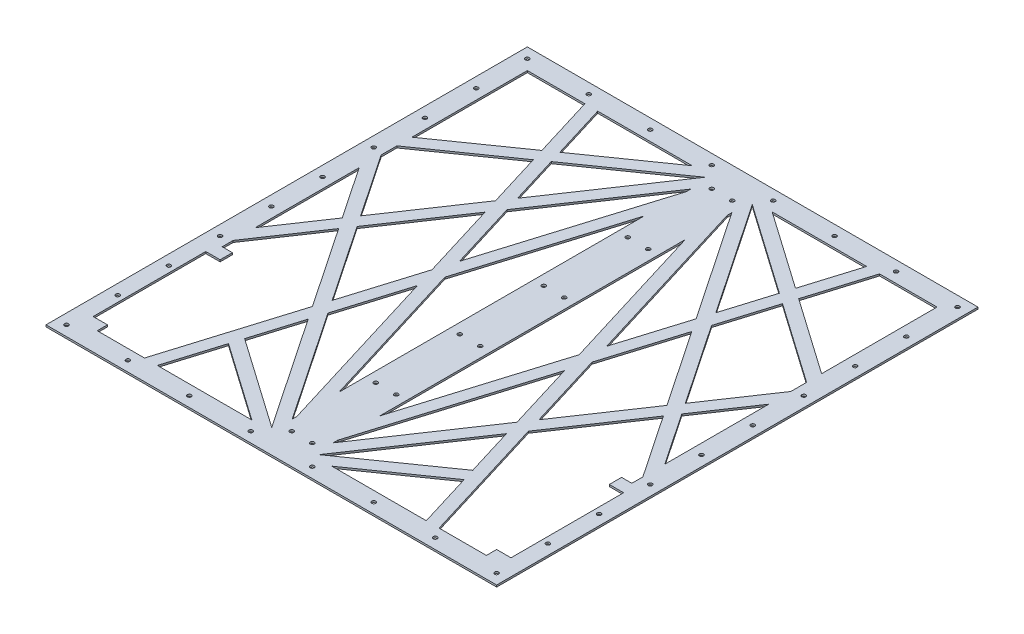
SolidWorks part; units mm, degrees
material "1060 Alloy"
ref_plane "Front Plane" through (0, 0, 0) normal (0, 0, 1) x (1, 0, 0)
ref_plane "Top Plane" through (0, 0, 0) normal (0, 1, 0) x (1, 0, 0)
ref_plane "Right Plane" through (0, 0, 0) normal (1, 0, 0) x (0, 0, -1)
sketch "Sketch1" plane through (0, 0, 0) normal (0, 1, 0) x (1, 0, 0)
  line L1 (0, 0) -> (558.8, 0)
  line L2 (0, 0) -> (0, 596.9)
  line L3 (0, 596.9) -> (558.8, 596.9)
  line L4 (558.8, 0) -> (558.8, 596.9)
  dimension "D1" = 596.9
  dimension "D2" = 558.8
extrude "Boss-Extrude1" add sketch "Sketch1" along normal blind 2.286 contours L2 L3 L4 L1
sketch "Sketch2" plane through (0, 2.286, 0) normal (0, 1, 0) x (1, 0, 0)
  line L0 (0, 0) -> (558.8, 0) construction
  line L1 (538.48, 38.1) -> (520.7, 38.1)
  line L2 (538.48, 38.1) -> (538.48, 177.8)
  line L3 (538.48, 177.8) -> (520.7, 177.8)
  line L4 (495.3, 76.2) -> (495.3, 139.7)
  line L5 (558.8, 0) -> (558.8, 596.9) construction
  line L6 (520.7, 177.8) -> (495.3, 139.7)
  line L7 (520.7, 38.1) -> (495.3, 76.2)
  dimension "D1" = 38.1
  dimension "D2" = 20.32
  dimension "D3" = 43.18
  dimension "D4" = 139.7
  dimension "D5" = 25.4
  dimension "D6" = 38.1
  dimension "D7" = 38.1
extrude "Cut-Extrude1" cut sketch "Sketch2" against normal through all
sketch "Sketch3" plane through (0, 2.286, 0) normal (0, 1, 0) x (1, 0, 0)
  line L0 (279.4, 596.9) -> (279.4, 0) construction
  line L1 (0, 596.9) -> (558.8, 596.9) construction
  line L2 (0, 0) -> (558.8, 0) construction
  line L3 (533.4, 571.5) -> (304.8, 571.5)
  line L4 (304.8, 571.5) -> (304.8, 25.4)
  line L5 (304.8, 25.4) -> (510.8505, 25.4)
  line L6 (510.8505, 25.4) -> (480.06, 71.5857)
  line L7 (480.06, 71.5857) -> (480.06, 144.3143)
  line L8 (480.06, 144.3143) -> (512.5438, 193.04)
  line L9 (512.5438, 193.04) -> (533.4, 193.04)
  line L10 (533.4, 193.04) -> (533.4, 571.5)
  line L11 (558.8, 0) -> (558.8, 596.9) construction
  line L12 (538.48, 177.8) -> (520.7, 177.8) construction
  line L14 (495.3, 139.7) -> (495.3, 76.2) construction
  line L15 (495.3, 76.2) -> (520.7, 38.1) construction
  line L16 (520.7, 177.8) -> (495.3, 139.7) construction
  dimension "D1" = 25.4
  dimension "D2" = 25.4
  dimension "D3" = 25.4
  dimension "D4" = 25.4
  dimension "D5" = 15.24
  dimension "D6" = 15.24
  dimension "D7" = 15.24
  dimension "D8" = 15.24
sketch "Sketch4" plane through (0, 2.286, 0) normal (0, 1, 0) x (1, 0, 0)
  line L0 (279.4, 0) -> (739.5052, 322.1692) construction
  line L1 (0, 0) -> (558.8, 0) construction
  line L3 (279.4, 0) -> (752.0221, 700.6911) construction
  line L5 (279.4, 0) -> (585.8425, 1002.3282) construction
  line L7 (279.4, 596.9) -> (1502.9036, -259.8065) construction
  line L8 (0, 596.9) -> (558.8, 596.9) construction
  line L9 (279.4, 596.9) -> (1021.4817, -503.2813) construction
  line L11 (279.4, 596.9) -> (643.6376, -594.4676) construction
  line L13 (286.687, -2.2279) -> (593.1295, 1000.1003)
  line L14 (285.7173, -4.261) -> (758.3394, 696.43)
  line L15 (283.7707, -6.2419) -> (738.0104, 311.8202)
  line L16 (272.113, 594.6721) -> (636.3506, -596.6955)
  line L17 (273.0827, 592.639) -> (1015.1644, -507.5424)
  line L18 (275.0293, 590.6581) -> (1498.533, -266.0484)
  line L19 (272.113, 2.2279) -> (578.5554, 1004.556)
  line L20 (273.0827, 4.261) -> (745.7048, 704.9521)
  line L21 (275.0293, 6.2419) -> (729.2691, 324.304)
  line L22 (286.687, 599.1279) -> (650.9247, -592.2397)
  line L23 (285.7173, 601.161) -> (1027.7989, -499.0203)
  line L24 (283.7707, 603.1419) -> (1507.2743, -253.5645)
  line L25 (279.4, 0) -> (733.6397, 318.0621) construction
  dimension "D1" = 35
  dimension "D2" = 56
  dimension "D3" = 73
  dimension "D4" = 35
  dimension "D5" = 56
  dimension "D6" = 73
  dimension "D7" = 7.62
  dimension "D8" = 7.62
sketch "Sketch5" plane through (0, 2.286, 0) normal (0, 1, 0) x (1, 0, 0)
  line L0 (510.8505, 25.4) -> (480.06, 71.5857)
  line L1 (480.06, 71.5857) -> (480.06, 131.2013)
  line L2 (480.06, 71.5857) -> (480.06, 144.3143) construction
  line L3 (283.7707, -6.2419) -> (738.0104, 311.8202) construction
  line L4 (480.06, 131.2013) -> (438.6182, 102.1835)
  line L5 (286.687, 599.1279) -> (650.9247, -592.2397) construction
  line L6 (438.6182, 102.1835) -> (462.0933, 25.4)
  line L7 (304.8, 25.4) -> (510.8505, 25.4) construction
  line L8 (462.0933, 25.4) -> (510.8505, 25.4)
  line L9 (328.96, 25.4) -> (446.1569, 25.4)
  line L10 (272.113, 594.6721) -> (636.3506, -596.6955) construction
  line L11 (446.1569, 25.4) -> (425.4919, 92.9923)
  line L12 (425.4919, 92.9923) -> (328.96, 25.4)
  line L13 (420.8068, 108.3164) -> (402.3567, 168.664)
  line L14 (275.0293, 6.2419) -> (729.2691, 324.304) construction
  line L15 (285.7173, -4.261) -> (758.3394, 696.43) construction
  line L16 (402.3567, 168.664) -> (308.7078, 29.8239)
  line L17 (308.7078, 29.8239) -> (420.8068, 108.3164)
  line L18 (433.9331, 117.5076) -> (486.9263, 154.6138)
  line L19 (520.7, 177.8) -> (495.3, 139.7) construction
  line L20 (486.9263, 154.6138) -> (512.5438, 193.04)
  line L21 (512.5438, 193.04) -> (533.4, 193.04)
  line L22 (533.4, 193.04) -> (533.4, 206.7027)
  line L23 (533.4, 193.04) -> (533.4, 571.5) construction
  line L24 (273.0827, 592.639) -> (1015.1644, -507.5424) construction
  line L25 (533.4, 206.7027) -> (480.7071, 284.8232)
  line L26 (480.7071, 284.8232) -> (413.3226, 184.9216)
  line L27 (413.3226, 184.9216) -> (433.9331, 117.5076)
  line L28 (533.4, 233.9563) -> (533.4, 362.9437)
  line L29 (285.7173, 601.161) -> (1027.7989, -499.0203) construction
  line L30 (533.4, 362.9437) -> (489.8984, 298.45)
  line L31 (489.8984, 298.45) -> (533.4, 233.9563)
  line L32 (407.5891, 203.675) -> (378.6135, 298.45)
  line L33 (273.0827, 4.261) -> (745.7048, 704.9521) construction
  line L34 (286.687, -2.2279) -> (593.1295, 1000.1003) construction
  line L35 (378.6135, 298.45) -> (407.5891, 393.225)
  line L36 (407.5891, 393.225) -> (471.5157, 298.45)
  line L37 (471.5157, 298.45) -> (407.5891, 203.675)
  line L38 (304.8, 51.2838) -> (304.8, 57.0169)
  line L39 (304.8, 571.5) -> (304.8, 25.4) construction
  line L40 (304.8, 57.0169) -> (370.6453, 272.3873)
  line L41 (370.6453, 272.3873) -> (396.6232, 187.4174)
  line L42 (396.6232, 187.4174) -> (304.8, 51.2838)
  line L43 (362.6772, 298.45) -> (304.8, 109.1424)
  line L44 (272.113, 2.2279) -> (578.5554, 1004.556) construction
  line L45 (304.8, 109.1424) -> (304.8, 487.7576)
  line L46 (304.8, 487.7576) -> (362.6772, 298.45)
  line L47 (480.7071, 312.0768) -> (533.4, 390.1973)
  line L48 (533.4, 390.1973) -> (533.4, 409.745)
  line L49 (275.0293, 590.6581) -> (1498.533, -266.0484) construction
  line L50 (533.4, 409.745) -> (433.9331, 479.3924)
  line L51 (433.9331, 479.3924) -> (413.3226, 411.9784)
  line L52 (413.3226, 411.9784) -> (480.7071, 312.0768)
  line L53 (370.6453, 324.5127) -> (396.6232, 409.4826)
  line L54 (396.6232, 409.4826) -> (304.8, 545.6162)
  line L55 (304.8, 545.6162) -> (304.8, 539.8831)
  line L56 (304.8, 539.8831) -> (370.6453, 324.5127)
  line L57 (308.7078, 567.0761) -> (402.3567, 428.236)
  line L58 (402.3567, 428.236) -> (420.8068, 488.5836)
  line L59 (420.8068, 488.5836) -> (308.7078, 567.0761)
  line L60 (533.4, 428.3496) -> (533.4, 571.5)
  line L61 (283.7707, 603.1419) -> (1507.2743, -253.5645) construction
  line L62 (533.4, 571.5) -> (462.0933, 571.5)
  line L63 (533.4, 571.5) -> (304.8, 571.5) construction
  line L64 (462.0933, 571.5) -> (438.6182, 494.7165)
  line L65 (438.6182, 494.7165) -> (533.4, 428.3496)
  line L66 (425.4919, 503.9077) -> (446.1569, 571.5)
  line L67 (446.1569, 571.5) -> (328.96, 571.5)
  line L68 (328.96, 571.5) -> (425.4919, 503.9077)
extrude "Cut-Extrude2" cut sketch "Sketch5" against normal up to next
ref_plane "Plane2" through (279.4, 0, 0) normal (-1, 0, 0) x (0, 0, 1)
mirror "Mirror1" about plane through (279.4, 0, 0) normal (-1, 0, 0) of "Cut-Extrude1", "Cut-Extrude2"
sketch "Sketch7" plane through (0, 0, 0) normal (0, -1, 0) x (1, 0, 0)
  line L0 (558.8, 0) -> (558.8, -25.4)
  line L1 (0, 0) -> (558.8, 0) construction
  line L2 (558.8, 0) -> (558.8, -596.9) construction
  line L3 (558.8, -25.4) -> (564.6477, -25.4)
  line L4 (564.6477, -25.4) -> (564.6477, 0)
  line L5 (564.6477, 0) -> (558.8, 0)
  line L6 (558.8, -233.68) -> (567.1239, -233.68)
  line L7 (567.1239, -233.68) -> (567.1239, -208.28)
  line L8 (567.1239, -208.28) -> (558.8, -208.28)
  line L9 (558.8, -208.28) -> (558.8, -233.68)
  line L10 (558.8, -429.26) -> (564.6477, -429.26)
  line L11 (564.6477, -429.26) -> (564.6477, -403.86)
  line L12 (564.6477, -403.86) -> (558.8, -403.86)
  line L13 (558.8, -403.86) -> (558.8, -429.26)
  line L14 (558.8, -571.5) -> (564.6477, -571.5)
  line L15 (564.6477, -571.5) -> (564.6477, -546.1)
  line L16 (564.6477, -546.1) -> (558.8, -546.1)
  line L17 (558.8, -546.1) -> (558.8, -571.5)
sketch "Sketch8" plane through (0, 0, 0) normal (0, -1, 0) x (1, 0, 0)
  line L0 (0, 0) -> (558.8, 0) construction
  line L1 (0, 0) -> (0, -596.9) construction
  circle A0 centre (12.7, -12.7) radius 2.4638
  dimension "D1" = 12.7
  dimension "D2" = 12.7
  dimension "D3" = 4.9276
extrude "Cut-Extrude3" cut sketch "Sketch8" against normal through all
pattern_linear "LPattern1" count 8 spacing 76.2 along (1, 0, 0) of "Cut-Extrude3"
pattern_linear "LPattern2" count 2 spacing 571.5 along (0, 0, -1) of "LPattern1", "Cut-Extrude3"
pattern_linear "LPattern3" count 9 spacing 63.5 along (0, 0, -1) of "Cut-Extrude3"
pattern_linear "LPattern4" count 2 spacing 533.4 along (1, 0, 0) of "LPattern3"
sketch "Sketch9" plane through (0, 0, 0) normal (0, -1, 0) x (1, 0, 0)
  line L0 (112.6431, -25.4) -> (229.84, -25.4) construction
  line L1 (254, -51.2838) -> (254, -57.0169) construction
  line L2 (304.8, -51.2838) -> (304.8, -57.0169) construction
  circle A0 centre (266.7, -38.1) radius 2.4638
  circle A1 centre (292.1, -38.1) radius 2.4638
  point P11 (304.8, -54.1504)
  dimension "D1" = 12.7
  dimension "D3" = 12.7
  dimension "D4" = 4.9276
  dimension "D2" = 12.7
extrude "Cut-Extrude4" cut sketch "Sketch9" against normal through all
pattern_linear "LPattern5" count 6 spacing 104.14 along (0, 0, -1) of "Cut-Extrude4"
sketch "Sketch10" plane through (0, 0, 0) normal (0, -1, 0) x (1, 0, 0)
  line L0 (116.675, -90.7132) -> (120.1818, -102.1835)
  line L1 (120.1818, -102.1835) -> (124.8669, -117.5076)
  line L2 (124.8669, -117.5076) -> (71.8737, -154.6138)
  line L3 (71.8737, -154.6138) -> (46.2562, -193.04)
  line L4 (46.2562, -193.04) -> (38.1, -193.04)
  line L5 (25.4, -193.04) -> (46.2562, -193.04) construction
  line L6 (38.1, -193.04) -> (38.1, -177.8)
  line L7 (38.1, -177.8) -> (38.1, -25.4)
  line L8 (38.1, -25.4) -> (47.9495, -25.4)
  line L9 (47.9495, -25.4) -> (96.7067, -25.4)
  line L11 (96.7067, -25.4) -> (116.675, -90.7132)
  line L13 (96.7067, -25.4) -> (120.1818, -102.1835) construction
extrude "Cut-Extrude5" cut sketch "Sketch10" against normal up to next
ref_plane "Plane3" through (279.4, 0, 0) normal (-1, 0, 0) x (0, 0, 1)
mirror "Mirror2" about plane through (279.4, 0, 0) normal (-1, 0, 0) of "Cut-Extrude5"
